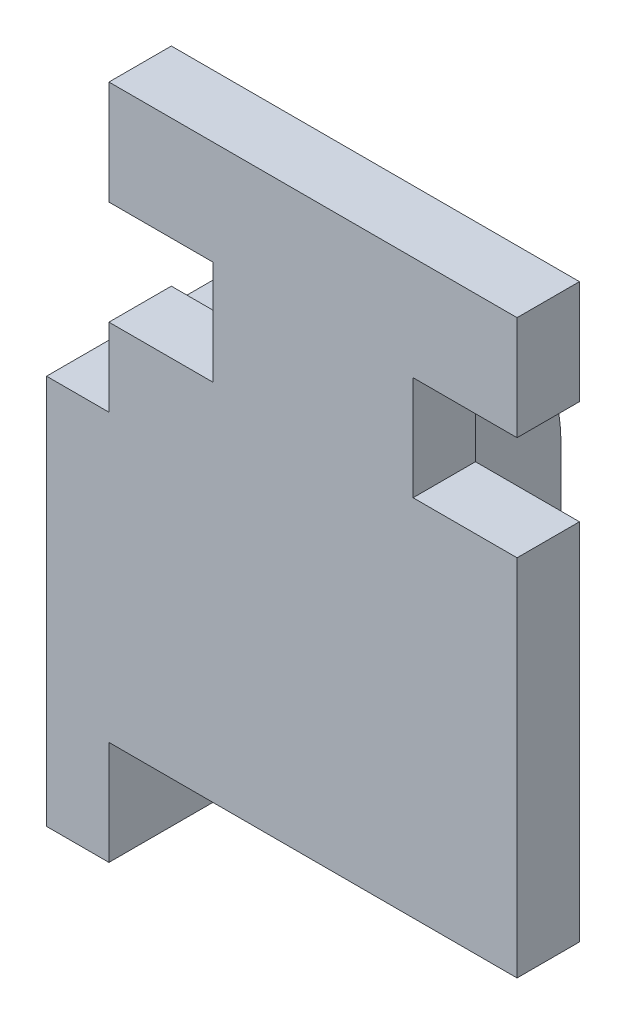
SolidWorks part; units mm, degrees
material "PBT General Purpose"
ref_plane "Front Plane" through (0, 0, 0) normal (0, 0, 1) x (1, 0, 0)
ref_plane "Top Plane" through (0, 0, 0) normal (0, 1, 0) x (1, 0, 0)
ref_plane "Right Plane" through (0, 0, 0) normal (1, 0, 0) x (0, 0, -1)
sketch "Sketch1" plane through (0, 0, 0) normal (0, 0, 1) x (1, 0, 0)
  line L0 (0, 0) -> (0, 1.4)
  line L1 (0, 1.4) -> (0.4, 1.4)
  line L2 (0.4, 1.4) -> (0.4, 1.8)
  line L3 (0.4, 1.8) -> (0, 1.8)
  line L4 (0, 1.8) -> (0, 2.2)
  line L5 (0, 2.2) -> (1.57, 2.2)
  line L6 (1.57, 2.2) -> (1.57, 1.8)
  line L7 (1.57, 1.8) -> (1.17, 1.8)
  line L8 (1.17, 1.8) -> (1.17, 1.4)
  line L9 (1.17, 1.4) -> (1.57, 1.4)
  line L10 (1.57, 1.4) -> (1.57, 0)
  line L11 (1.57, 0) -> (0, 0)
  dimension "D1" = 0.4
  dimension "D2" = 0.4
  dimension "D3" = 0.77
  dimension "D4" = 0.4
  dimension "D5" = 0.4
  dimension "D6" = 1.4
  dimension "D7" = 0.4
extrude "Boss-Extrude1" add sketch "Sketch1" along normal blind 0.24
sketch "Sketch2" plane through (0, 0, 0) normal (-1, 0, 0) x (0, 0, 1)
  line L0 (0.24, 0) -> (0.24, -0.4)
  line L2 (-1.5, -0.4) -> (0.24, -0.4)
  line L3 (-1.5, -0.4) -> (-1.5, 1.1)
  line L4 (-1.5, 1.1) -> (0, 1.1)
  line L5 (0, 1.4) -> (0, 0) construction
  line L6 (0, 1.1) -> (0.24, 1.1)
  line L7 (0.24, 1.4) -> (0.24, 0) construction
  line L8 (0.24, 1.1) -> (0.24, 0)
  line L9 (0.24, 1.4) -> (0, 1.4) construction
  point P5 (0.24, -0.358)
  dimension "D1" = 0.3
  dimension "D2" = 1.5
  dimension "D3" = 1.5
extrude "Boss-Extrude2" add sketch "Sketch2" along normal blind 0.24
fillet "Fillet1" radius 1 1 edges at (-0.12, 1.1, -1.5)
